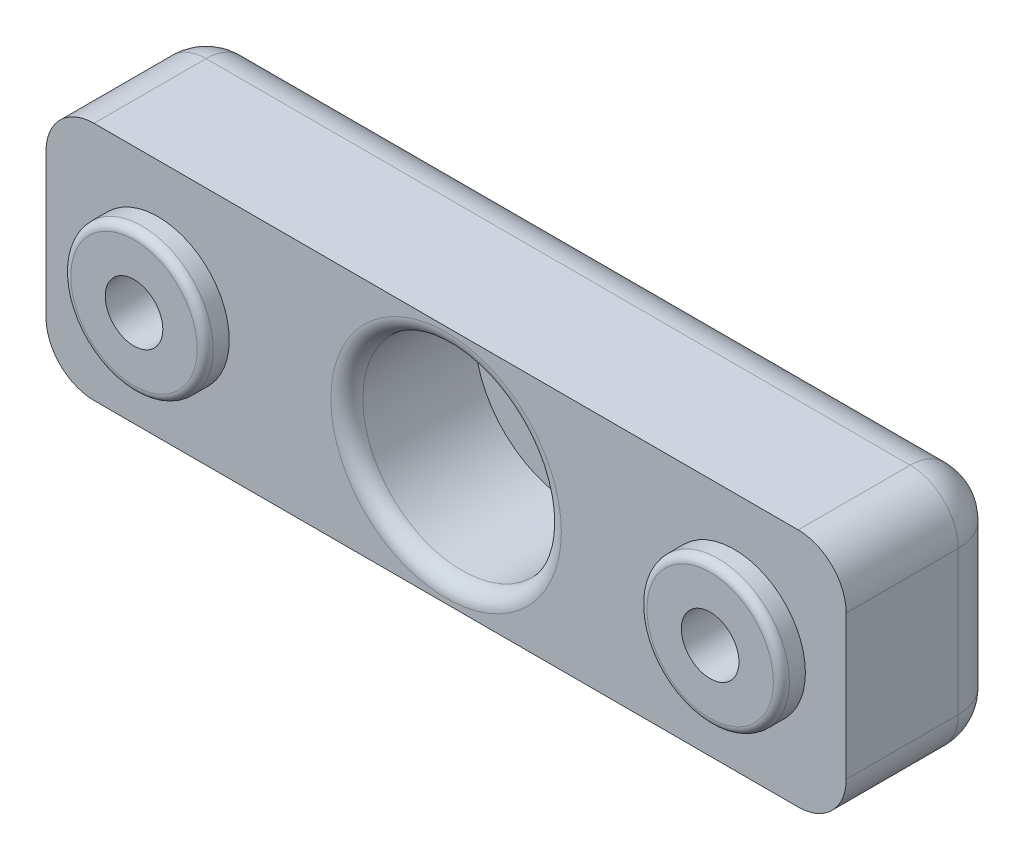
SolidWorks part; units mm, degrees
ref_plane "Alzado" through (0, 0, 0) normal (0, 0, 1) x (1, 0, 0)
ref_plane "Planta" through (0, 0, 0) normal (0, 1, 0) x (1, 0, 0)
ref_plane "Vista lateral" through (0, 0, 0) normal (1, 0, 0) x (0, 0, -1)
sketch "Croquis1" plane through (0, 0, 0) normal (0, 0, 1) x (1, 0, 0)
  line L1 (-27.43, 16.0979) -> (22.57, 16.0979)
  line L2 (-27.43, 16.0979) -> (-27.43, 1.0979)
  line L3 (-27.43, 1.0979) -> (22.57, 1.0979)
  line L4 (22.57, 16.0979) -> (22.57, 1.0979)
  dimension "D1" = 50
  dimension "D2" = 15
extrude "Saliente-Extruir1" add sketch "Croquis1" along normal blind 10
sketch "Croquis2" plane through (0, 0, 10) normal (0, 0, 1) x (1, 0, 0)
  line L0 (-27.43, 1.0979) -> (22.57, 16.0979) construction
  line L1 (22.57, 16.0979) -> (-27.43, 16.0979) construction
  line L2 (22.57, 1.0979) -> (22.57, 16.0979) construction
  circle A0 centre (-2.43, 8.5979) radius 6.2
  circle A1 centre (-20.43, 8.5979) radius 4.45
  circle A2 centre (15.57, 8.5979) radius 4.45
  dimension "D1" = 12.4
  dimension "D2" = 8.9
  dimension "D3" = 8.9
  dimension "D4" = 18
  dimension "D5" = 18
extrude "Saliente-Extruir2" add sketch "Croquis2" along normal blind 1.5
sketch "Croquis3" plane through (0, 0, 11.5) normal (0, 0, 1) x (1, 0, 0)
  circle A1 centre (-2.43, 8.5979) radius 6.2
  circle A2 centre (-2.43, 8.5979) radius 6.2
  dimension "D1" = 0
extrude "Cortar-Extruir1" cut sketch "Croquis3" against normal blind 9.5
sketch "Croquis4" plane through (0, 0, 11.5) normal (0, 0, 1) x (1, 0, 0)
  circle A0 centre (-20.43, 8.5979) radius 1.8
  circle A1 centre (15.57, 8.5979) radius 1.8
  dimension "D1" = 3.6
  dimension "D2" = 3.6
extrude "Cortar-Extruir2" cut sketch "Croquis4" against normal blind 15.5
sketch "Croquis5" plane through (0, 0, 0) normal (0, 0, -1) x (-1, 0, 0)
  line L1 (-12.0482, 8.5979) -> (-13.8091, 11.6479)
  line L2 (-13.8091, 11.6479) -> (-17.3309, 11.6479)
  line L3 (-17.3309, 11.6479) -> (-19.0918, 8.5979)
  line L4 (-19.0918, 8.5979) -> (-17.3309, 5.5479)
  line L5 (-17.3309, 5.5479) -> (-13.8091, 5.5479)
  line L6 (-13.8091, 5.5479) -> (-12.0482, 8.5979)
  line L7 (23.9518, 8.5979) -> (22.1909, 11.6479)
  line L8 (22.1909, 11.6479) -> (18.6691, 11.6479)
  line L9 (18.6691, 11.6479) -> (16.9082, 8.5979)
  line L10 (16.9082, 8.5979) -> (18.6691, 5.5479)
  line L11 (18.6691, 5.5479) -> (22.1909, 5.5479)
  line L12 (22.1909, 5.5479) -> (23.9518, 8.5979)
  circle A0 centre (-15.57, 8.5979) radius 3.05 construction
  circle A1 centre (20.43, 8.5979) radius 3.05 construction
  dimension "D1" = 6.1
  dimension "D2" = 6.1
extrude "Cortar-Extruir3" cut sketch "Croquis5" against normal blind 3.5
fillet "Redondeo1" radius 3 8 edges at (-2.43, 1.0979, 0) (22.57, 1.0979, 5) (22.57, 16.0979, 5) (22.57, 8.5979, 0) (-27.43, 1.0979, 5) (-27.43, 8.5979, 0) (-27.43, 16.0979, 5) (-2.43, 16.0979, 0)
fillet "Redondeo2" radius 1 1 edges at (3.77, 8.5979, 10)
fillet "Redondeo3" radius 0.5 2 edges at (20.02, 8.5979, 11.5) (-15.98, 8.5979, 11.5)
